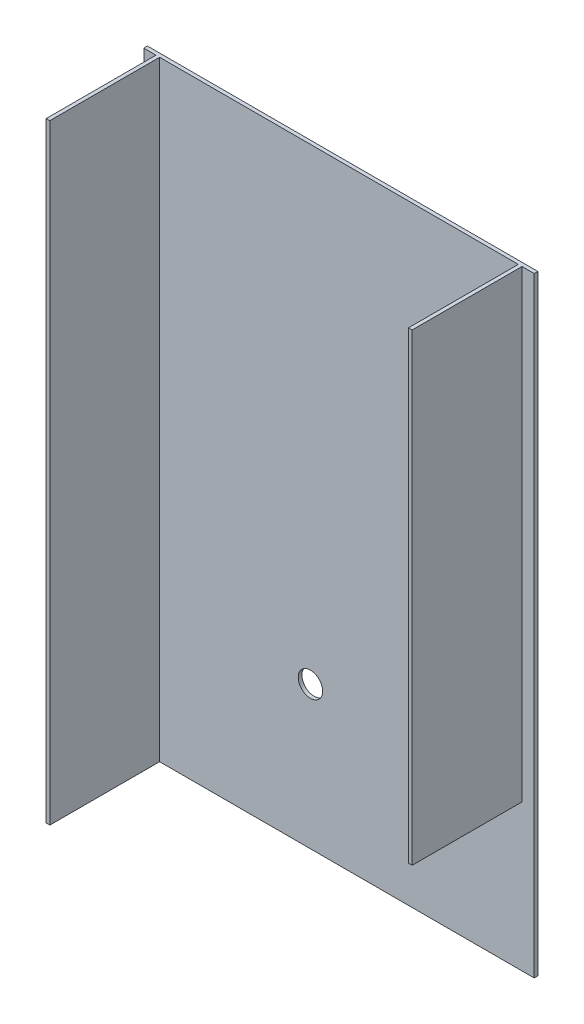
SolidWorks part; units mm, degrees
ref_plane "Front Plane" through (0, 0, 0) normal (0, 0, 1) x (1, 0, 0)
ref_plane "Top Plane" through (0, 0, 0) normal (0, 1, 0) x (1, 0, 0)
ref_plane "Right Plane" through (0, 0, 0) normal (1, 0, 0) x (0, 0, -1)
sketch "Sketch3" plane through (0, 0, 0) normal (0, 0, 1) x (1, 0, 0)
  line L1 (-80, 125) -> (80, 125)
  line L2 (-80, 125) -> (-80, -125)
  line L3 (-80, -125) -> (80, -125)
  line L4 (80, 125) -> (80, -125)
  line L5 (-80, 125) -> (80, -125) construction
  line L6 (-80, -125) -> (80, 125) construction
  point P0 (0, 0)
  dimension "D1" = 160
  dimension "D2" = 250
extrude "Boss-Extrude2" add sketch "Sketch3" along normal blind 1.5
sketch "Sketch4" plane through (0, 0, 0) normal (0, 0, 1) x (1, 0, 0)
  line L0 (-80, 125) -> (-80, -125) construction
  line L1 (-80, -125) -> (80, -125) construction
  circle A0 centre (-11.69, -66.6) radius 5
  dimension "D1" = 10
  dimension "D2" = 68.31
  dimension "D3" = 58.4
extrude "Cut-Extrude4" cut sketch "Sketch4" along normal through all
sketch "Sketch6" plane through (0, 0, 1.5) normal (0, 0, 1) x (1, 0, 0)
  line L1 (73.5, 51.3103) -> (73.5, 55.9673)
  line L3 (80, 125) -> (-80, 125) construction
  line L4 (-73.5, 125) -> (-75, 125)
  line L5 (-73.5, 125) -> (-73.5, -125)
  line L6 (-73.5, -125) -> (-75, -125)
  line L7 (-75, 125) -> (-75, -125)
  line L8 (-80, -125) -> (80, -125) construction
  line L9 (-80, 125) -> (-80, -125) construction
  line L10 (73.5, 125) -> (75, 125)
  line L11 (73.5, 125) -> (73.5, -65)
  line L12 (73.5, -65) -> (75, -65)
  line L13 (75, 125) -> (75, -65)
  line L14 (80, -125) -> (80, 125) construction
  line L16 (2.2297, 18.8238) -> (70.0068, 68.0582)
  line L23 (2.2297, 18.8238) -> (3.1113, 17.6102)
  line L25 (70.0068, 68.0582) -> (72.6184, 69.9553)
  line L26 (73.5, 68.7417) -> (72.6184, 69.9553)
  line L27 (-38.6728, -9.9336) -> (-39.54, -11.1294)
  line L28 (-73.5, 13.5) -> (-39.54, -11.1294)
  line L29 (-38.6728, -9.9336) -> (-72.8438, 14.8489)
  line L30 (-73.5, 13.5) -> (-72.8438, 14.8489)
  line L31 (60.5, -106.225) -> (75, -120) construction
  line L32 (-56.52, 1.1853) -> (-60.0426, -3.6718) construction
  line L33 (61.8775, -104.775) -> (76.3775, -118.55)
  line L34 (59.1225, -107.675) -> (73.6225, -121.45)
  line L35 (-54.901, 0.0111) -> (-58.4236, -4.846)
  line L36 (-58.139, 2.3595) -> (-61.6616, -2.4976)
  line L37 (73.5, 68.7417) -> (3.1113, 17.6102)
  line L38 (38.3056, 43.176) -> (50.06, 26.9947) construction
  line L39 (39.9238, 44.3514) -> (51.6781, 28.1701)
  line L40 (36.6875, 42.0005) -> (48.4419, 25.8192)
  line L46 (45, -90) -> (70, -90) construction
  line L47 (45, -88) -> (70, -88)
  line L48 (45, -92) -> (70, -92)
  line L50 (-69.2966, -15.1235) -> (-58.4236, -15.1235)
  line L51 (-69.2966, -15.1235) -> (-69.2966, -26.8765)
  line L52 (-69.2966, -26.8765) -> (-58.4236, -26.8765)
  line L53 (-58.4236, -15.1235) -> (-58.4236, -26.8765)
  circle A0 centre (-11.69, -66.6) radius 58.31
  arc A1 (61.8775, -104.775) -> (59.1225, -107.675) centre (60.5, -106.225) ccw
  arc A2 (73.6225, -121.45) -> (76.3775, -118.55) centre (75, -120) ccw
  arc A3 (-54.901, 0.0111) -> (-58.139, 2.3595) centre (-56.52, 1.1853) ccw
  arc A4 (-61.6616, -2.4976) -> (-58.4236, -4.846) centre (-60.0426, -3.6718) ccw
  arc A5 (39.9238, 44.3514) -> (36.6875, 42.0005) centre (38.3056, 43.176) ccw
  arc A6 (48.4419, 25.8192) -> (51.6781, 28.1701) centre (50.06, 26.9947) ccw
  arc A7 (45, -88) -> (45, -92) centre (45, -90) ccw
  arc A8 (70, -92) -> (70, -88) centre (70, -90) ccw
  point P20 (74.25, -65)
  point P36 (-58.2813, -1.2432)
  point P38 (67.75, -113.1125)
  point P47 (44.1828, 35.0853)
  point P60 (57.5, -90)
  point P65 (72, -90)
  point P66 (-69.2966, -21)
  line M12 (80, 125) -> (-80, 125)
  line M14 (-80, -125) -> (80, -125)
  dimension "D1" = 116.62
  dimension "D19" = 20
  dimension "D20" = 2
  dimension "D12" = 2
  dimension "D9" = 2
  dimension "D3" = 1.5
  dimension "D4" = 5
  dimension "D5" = 60
  dimension "D6" = 5
  dimension "D7" = 1.5
  dimension "D8" = 111.5
  dimension "D10" = 41.9871
  dimension "D11" = 50
  dimension "D13" = 6
  dimension "D14" = 19.9574
  dimension "D15" = 1.5
  dimension "D16" = 20
  dimension "D17" = 87
  dimension "D18" = 56.2583
  dimension "D21" = 5
  dimension "D22" = 5
  dimension "D23" = 19.5
  dimension "D24" = 23.48
  dimension "D25" = 121.3282
  dimension "D26" = 29.94
  dimension "D27" = 41.6944
  dimension "D28" = 81.824
  dimension "D29" = 2
  dimension "D30" = 25
  dimension "D31" = 10
  dimension "D32" = 104
  dimension "D33" = 35
extrude "Boss-Extrude4" add sketch "Sketch6" along normal blind 45 contours L7 L5 M12 M14 | L11 L12 L13 L10
sketch "Sketch7" plane through (0, 0, 0) normal (0, 0, 1) x (1, 0, 0)
